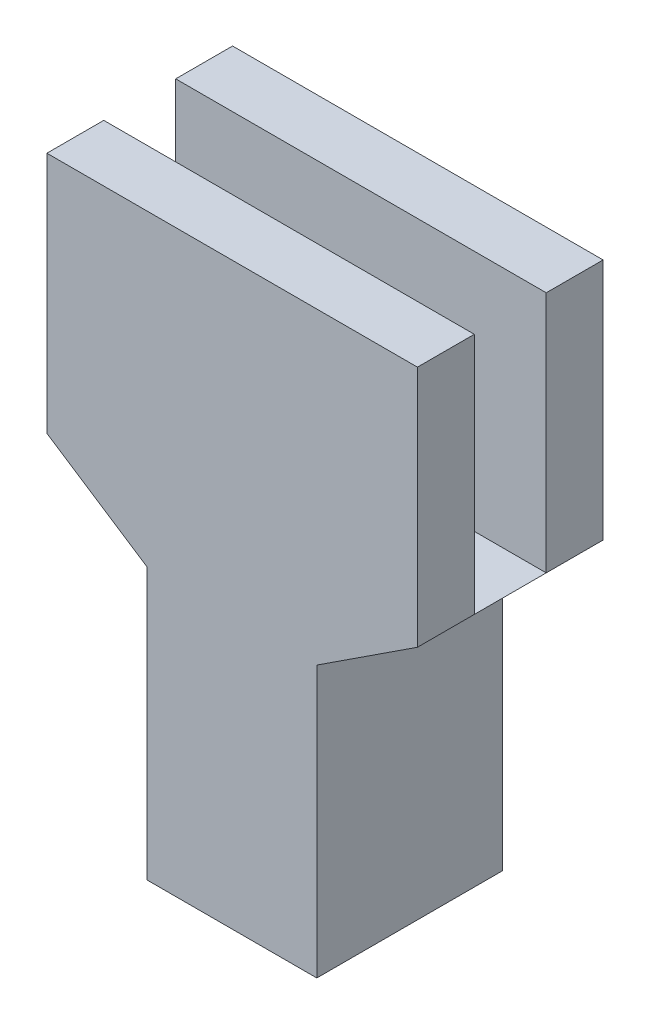
SolidWorks part; units mm, degrees
ref_plane "Спереди" through (0, 0, 0) normal (0, 0, 1) x (1, 0, 0)
ref_plane "Сверху" through (0, 0, 0) normal (0, 1, 0) x (1, 0, 0)
ref_plane "Справа" through (0, 0, 0) normal (1, 0, 0) x (0, 0, -1)
sketch "Эскиз1" plane through (0, 0, 0) normal (0, 0, 1) x (1, 0, 0)
  line L0 (29.1233, 63.4796) -> (68.8158, 63.4796) construction
  line L1 (0, 0) -> (0, 106.4506) construction
  line L2 (49.8925, 41.1227) -> (22.8241, 23.4364)
  line L3 (-22.9109, -49.5636) -> (22.793, -49.5636)
  line L5 (49.8925, 106.4506) -> (49.8925, 41.1227)
  line L6 (-49.8925, 106.4506) -> (49.8925, 106.4506)
  line L7 (-22.9109, 23.4364) -> (-22.9109, -49.5636)
  line L8 (-49.8925, 106.4506) -> (-49.8925, 41.1227)
  line L9 (22.8241, 23.4364) -> (22.793, -49.5636)
  line L18 (-49.8925, 41.1227) -> (-22.9109, 23.4364)
  point P0 (0, 0)
extrude "Вытянуть1" add sketch "Эскиз1" along normal blind 50
sketch "Sketch1" plane through (0, -49.5636, 0) normal (0, -1, 0) x (1, 0, 0)
  circle A0 centre (0, 25) radius 5
extrude "Cut-Extrude1" cut sketch "Sketch1" against normal blind 20
sketch "Sketch2" plane through (-49.8925, 0, 0) normal (-1, 0, 0) x (0, 0, 1)
  line L0 (25, 85.6506) -> (25, 119.2383) construction
  line L3 (15.3175, 188.28) -> (34.6825, 188.28)
  line L4 (15.3175, 188.28) -> (15.3175, 41.1227)
  line L5 (15.3175, 41.1227) -> (34.6825, 41.1227)
  line L6 (34.6825, 188.28) -> (34.6825, 41.1227)
  line L7 (15.3175, 188.28) -> (34.6825, 41.1227) construction
  line L8 (15.3175, 41.1227) -> (34.6825, 188.28) construction
  point P1 (25, 114.7013)
extrude "Cut-Extrude2" cut sketch "Sketch2" against normal through all
